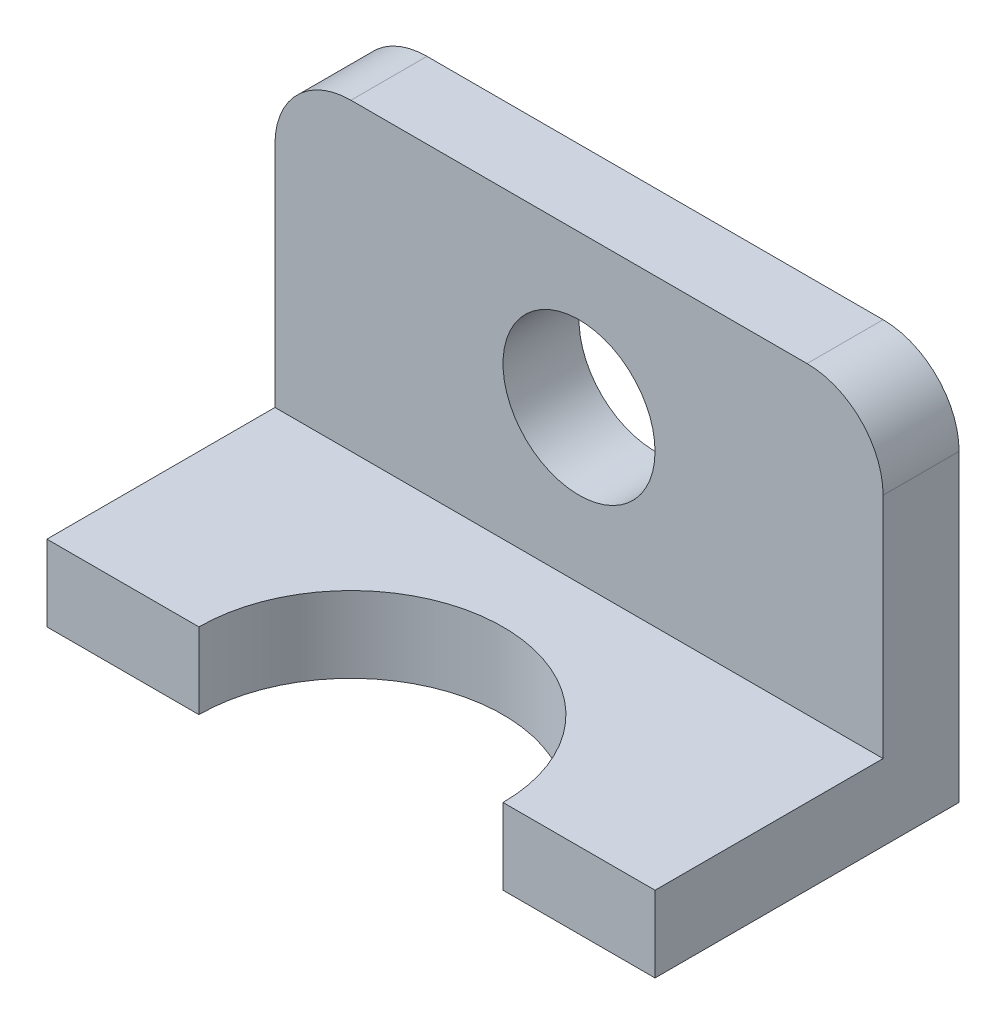
SolidWorks part; units mm, degrees
material "6061 Alloy"
ref_plane "Front Plane" through (0, 0, 0) normal (0, 0, 1) x (1, 0, 0)
ref_plane "Top Plane" through (0, 0, 0) normal (0, 1, 0) x (1, 0, 0)
ref_plane "Right Plane" through (0, 0, 0) normal (1, 0, 0) x (0, 0, -1)
sketch "Sketch1" plane through (0, 0, 0) normal (1, 0, 0) x (0, 0, -1)
  line L1 (0, 0) -> (50.8, 0)
  line L2 (0, 0) -> (0, 63.5)
  line L3 (0, 63.5) -> (50.8, 63.5)
  line L4 (50.8, 0) -> (50.8, 63.5)
  dimension "D1" = 50.8
  dimension "D2" = 63.5
extrude "Boss-Extrude1" add sketch "Sketch1" along normal mid plane 101.6
sketch "Sketch2" plane through (0, 0, 0) normal (1, 0, 0) x (0, 0, -1)
  line L0 (0, 12.7) -> (38.1, 12.7)
  line L1 (0, 63.5) -> (0, 0) construction
  line L2 (38.1, 12.7) -> (38.1, 63.5)
  line L3 (50.8, 63.5) -> (0, 63.5) construction
  line L4 (38.1, 63.5) -> (0, 63.5)
  line L5 (0, 63.5) -> (0, 12.7)
  line L6 (50.8, 0) -> (50.8, 63.5) construction
  dimension "D1" = 12.7
  dimension "D2" = 12.7
extrude "Cut-Extrude1" cut sketch "Sketch2" against normal through all and the other way through all
fillet "Fillet1" radius 12.7 2 edges at (-50.8, 63.5, -44.45) (50.8, 63.5, -44.45)
sketch "Sketch3" plane through (0, 12.7, 0) normal (0, 1, 0) x (1, 0, 0)
  circle A0 centre (0, 0) radius 25.4
  dimension "D1" = 50.8
extrude "Cut-Extrude2" cut sketch "Sketch3" against normal through all and the other way through all
hole_wizard "#97 (0.0059) Diameter Hole1" positions "Sketch4" profile "Sketch5" hole size "#97" standard "ANSI Inch" end condition through all
sketch "Sketch4" plane through (0, 0, -38.1) normal (0, 0, 1) x (1, 0, 0)
  line L0 (-50.8, 12.7) -> (50.8, 12.7) construction
  point P0 (0, 38.1)
  dimension "D1" = 25.4
sketch "Sketch5" plane through (0, 38.1, -38.1) normal (1, 0, 0) x (0, -1, 0)
  line L0 (0, 0) -> (0, 12.7)
  line L1 (0, 12.7) -> (12.7, 12.7)
  line L2 (12.7, 12.7) -> (12.7, 0)
  line L5 (12.7, 0) -> (0, 0)
  line L11 (0, -6.35) -> (0, 107.95) construction
  dimension "Thru Hole Dia." = 25.4
  dimension "Thru Hole Depth" = 12.7
